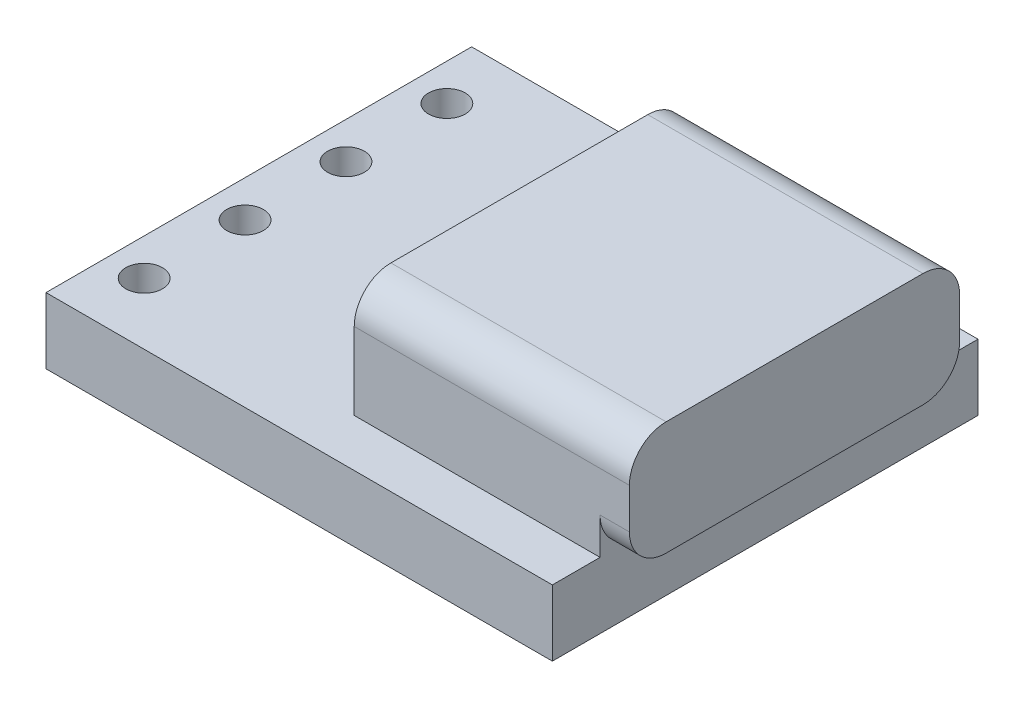
SolidWorks part; units mm, degrees
ref_plane "前视基准面" through (0, 0, 0) normal (0, 0, 1) x (1, 0, 0)
ref_plane "上视基准面" through (0, 0, 0) normal (0, 1, 0) x (1, 0, 0)
ref_plane "右视基准面" through (0, 0, 0) normal (1, 0, 0) x (0, 0, -1)
other "Configuration Table"
sketch "草图1" plane through (0, 0, 0) normal (0, 1, 0) x (1, 0, 0)
  line L1 (-6.9, 5.8) -> (6.9, 5.8)
  line L2 (-6.9, 5.8) -> (-6.9, -5.8)
  line L3 (-6.9, -5.8) -> (6.9, -5.8)
  line L4 (6.9, 5.8) -> (6.9, -5.8)
  line L5 (-6.9, 5.8) -> (6.9, -5.8) construction
  line L6 (-6.9, -5.8) -> (6.9, 5.8) construction
  point P0 (0, 0)
  dimension "D1" = 11.6
  dimension "D2" = 13.8
extrude "凸台-拉伸1" add sketch "草图1" along normal blind 1.8
sketch "草图4" plane through (0, 1.8, 0) normal (0, 1, 0) x (1, 0, 0)
  line L0 (0, 0) -> (9.5492, 0) construction
  line L1 (0.2, 4.5) -> (7.7, 4.5)
  line L2 (0.2, 4.5) -> (0.2, -4.5)
  line L3 (0.2, -4.5) -> (7.7, -4.5)
  line L4 (7.7, 4.5) -> (7.7, -4.5)
  line L5 (-6.9, 5.8) -> (-6.9, -5.8) construction
  dimension "D1" = 9
  dimension "D2" = 7.5
  dimension "D3" = 14.6
extrude "凸台-拉伸2" add sketch "草图4" along normal blind 4.9 from surface at -1.8 starting at face at (0, 0, 0)
sketch "草图5" plane through (7.7, 0, 0) normal (1, 0, 0) x (0, 0, -1)
  line L0 (-5.8, 1.8) -> (-4.5, 1.8) construction
  line L1 (-4.5, 1.8) -> (4.5, 1.8)
  line L2 (-4.5, 1.8) -> (-4.5, 0)
  line L3 (-4.5, 0) -> (4.5, 0)
  line L4 (4.5, 1.8) -> (4.5, 0)
  line L5 (4.5, 0) -> (5.8, 0) construction
  line L6 (-4.5, 1.8) -> (-4.5, 0) construction
  line L7 (4.5, 0) -> (4.5, 1.8) construction
extrude "切除-拉伸1" cut sketch "草图5" against normal up to surface (0.8 mm away) up to face at (6.9, 0.9, 5.15)
fillet "圆角1" radius 1 4 edges at (3.95, 4.9, -4.5) (3.95, 4.9, 4.5) (7.3, 1.8, -4.5) (7.3, 1.8, 4.5)
sketch "草图6" plane through (0, 1.8, 0) normal (0, 1, 0) x (1, 0, 0)
  line L0 (-6.9, 5.8) -> (-6.9, -5.8) construction
  line L1 (0, 0) -> (-7.9669, 0) construction
  circle A0 centre (-5.9, 4.125) radius 0.5
  circle A1 centre (-5.9, 1.375) radius 0.5
  circle A2 centre (-5.9, -1.375) radius 0.5
  circle A3 centre (-5.9, -4.125) radius 0.5
  dimension "D1" = 1
  dimension "D3" = 1
  dimension "D2" = 4
extrude "切除-拉伸2" cut sketch "草图6" against normal up to next
